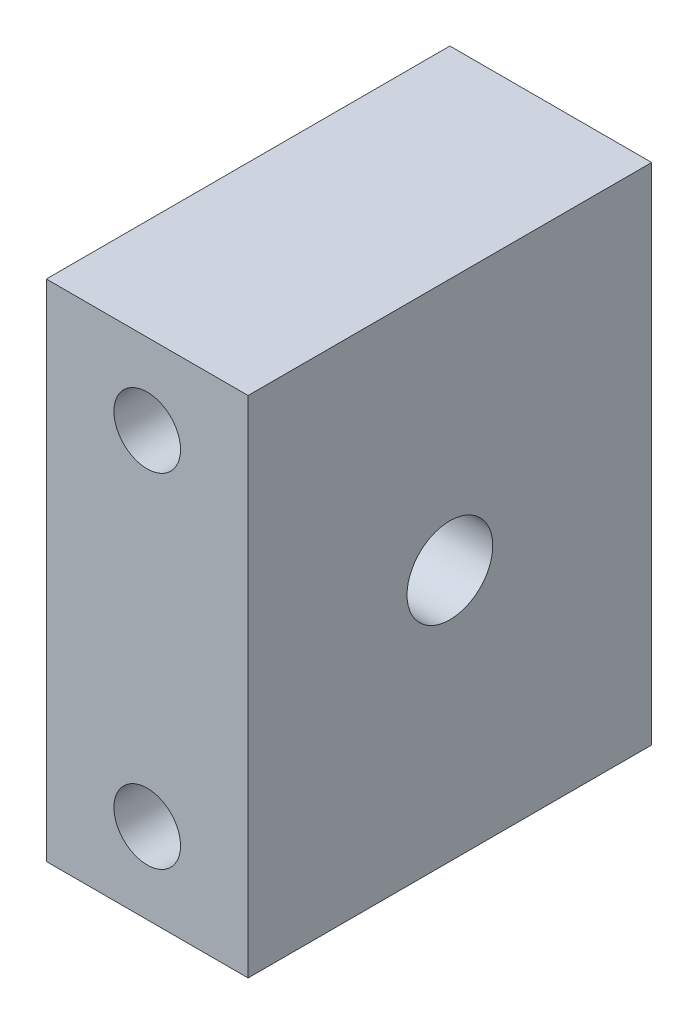
SolidWorks part; units mm, degrees
ref_plane "前视基准面" through (0, 0, 0) normal (0, 0, 1) x (1, 0, 0)
ref_plane "上视基准面" through (0, 0, 0) normal (0, 1, 0) x (1, 0, 0)
ref_plane "右视基准面" through (0, 0, 0) normal (1, 0, 0) x (0, 0, -1)
other "Configuration Table"
sketch "草图1" plane through (0, 0, 0) normal (0, 0, 1) x (1, 0, 0)
  line L1 (0, 0) -> (20, 0)
  line L2 (0, 0) -> (0, 50)
  line L3 (0, 50) -> (20, 50)
  line L4 (20, 0) -> (20, 50)
  circle A0 centre (10, 8) radius 3.3
  circle A1 centre (10, 42) radius 3.3
extrude "Screw_bracket_20x50x40" add sketch "草图1" along normal blind 40
sketch "草图2" plane through (0, 0, 0) normal (-1, 0, 0) x (0, 0, 1)
  circle A0 centre (20, 25) radius 4.25
extrude "M10_tap_pilot_8p5" cut sketch "草图2" against normal blind 20
